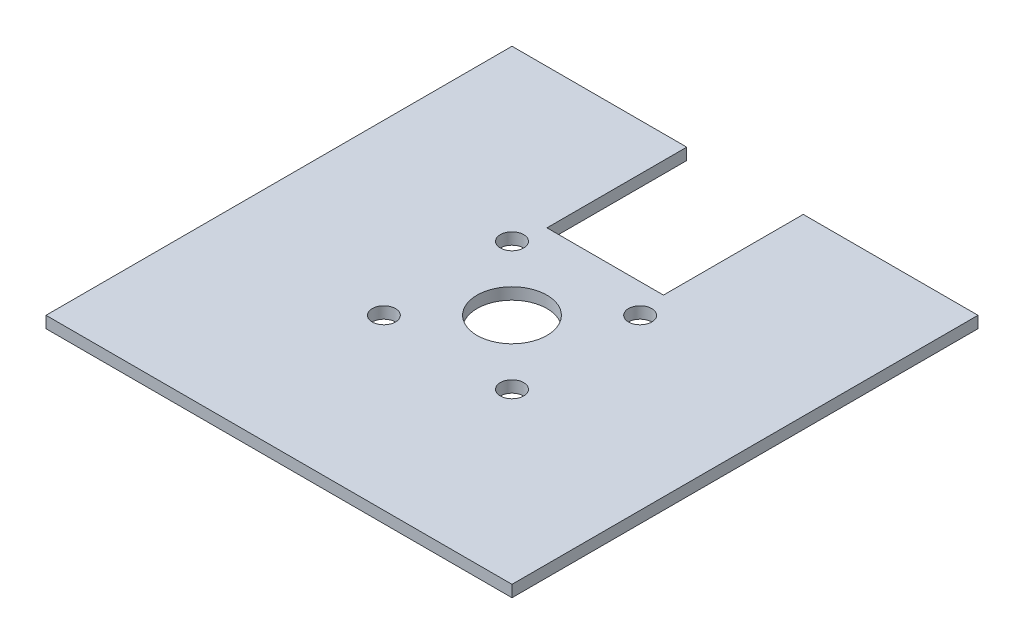
SolidWorks part; units mm, degrees
ref_plane "Front Plane" through (0, 0, 0) normal (0, 0, 1) x (1, 0, 0)
ref_plane "Top Plane" through (0, 0, 0) normal (0, 1, 0) x (1, 0, 0)
ref_plane "Right Plane" through (0, 0, 0) normal (1, 0, 0) x (0, 0, -1)
sketch "Sketch1" plane through (0, 0, 0) normal (0, 1, 0) x (1, 0, 0)
  line L0 (-319.1331, 0) -> (319.1331, 0) construction
  line L1 (0, -184.1073) -> (0, 184.1073) construction
  line L2 (-31.75, 50.8) -> (31.75, 50.8)
  line L3 (-127, -127) -> (127, -127)
  line L4 (-127, -127) -> (-127, 127)
  line L5 (-127, 127) -> (-31.75, 127)
  line L6 (127, -127) -> (127, 127)
  line L7 (-127, -127) -> (127, 127) construction
  line L8 (-127, 127) -> (127, -127) construction
  line L9 (-31.75, 50.8) -> (-31.75, 127)
  line L10 (31.75, 50.8) -> (31.75, 127)
  line L11 (31.75, 127) -> (127, 127)
  circle A0 centre (0, 0) radius 19.05
  circle A1 centre (-34.925, 34.925) radius 6.35
  circle A2 centre (34.925, 34.925) radius 6.35
  circle A3 centre (34.925, -34.925) radius 6.35
  circle A4 centre (-34.925, -34.925) radius 6.35
  point P0 (0, 0)
  point P4 (0, 0)
  point P8 (0, 0)
  point P26 (0, 50.8)
  dimension "D3" = 38.1
  dimension "D4" = 12.7
  dimension "D1" = 254
  dimension "D2" = 254
  dimension "D5" = 34.925
  dimension "D6" = 34.925
  dimension "D7" = 63.5
  dimension "D8" = 76.2
extrude "Boss-Extrude1" add sketch "Sketch1" along normal mid plane 6.35
